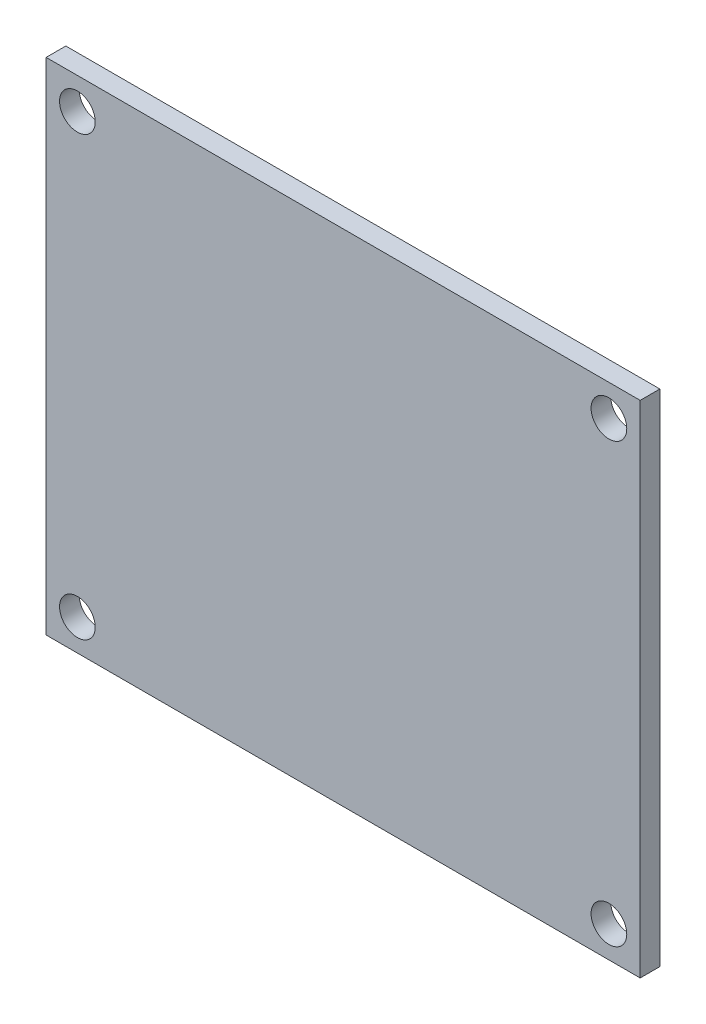
SolidWorks part; units mm, degrees
ref_plane "Front Plane" through (0, 0, 0) normal (0, 0, 1) x (1, 0, 0)
ref_plane "Top Plane" through (0, 0, 0) normal (0, 1, 0) x (1, 0, 0)
ref_plane "Right Plane" through (0, 0, 0) normal (1, 0, 0) x (0, 0, -1)
sketch "Sketch1" plane through (0, 0, 0) normal (0, 0, 1) x (1, 0, 0)
  line L1 (-24.13, 20.32) -> (24.13, 20.32)
  line L2 (-24.13, 20.32) -> (-24.13, -20.32)
  line L3 (-24.13, -20.32) -> (24.13, -20.32)
  line L4 (24.13, 20.32) -> (24.13, -20.32)
  line L5 (-24.13, 20.32) -> (24.13, -20.32) construction
  line L6 (-24.13, -20.32) -> (24.13, 20.32) construction
  line L7 (21.59, -17.78) -> (-21.59, -17.78) construction
  line L8 (21.59, -17.78) -> (21.59, 17.78) construction
  line L9 (21.59, 17.78) -> (-21.59, 17.78) construction
  line L10 (-21.59, -17.78) -> (-21.59, 17.78) construction
  line L11 (21.59, -17.78) -> (-21.59, 17.78) construction
  line L12 (21.59, 17.78) -> (-21.59, -17.78) construction
  circle A0 centre (-21.59, 17.78) radius 1.45
  circle A1 centre (21.59, 17.78) radius 1.45
  circle A2 centre (21.59, -17.78) radius 1.45
  circle A3 centre (-21.59, -17.78) radius 1.45
  point P0 (0, 0)
  point P6 (0, 0)
  dimension "D5" = 2.9
  dimension "D6" = 2.9
  dimension "D7" = 2.9
  dimension "D8" = 2.9
  dimension "D1" = 48.26
  dimension "D2" = 40.64
  dimension "D3" = 43.18
  dimension "D4" = 35.56
extrude "Boss-Extrude1" add sketch "Sketch1" along normal blind 1.6
